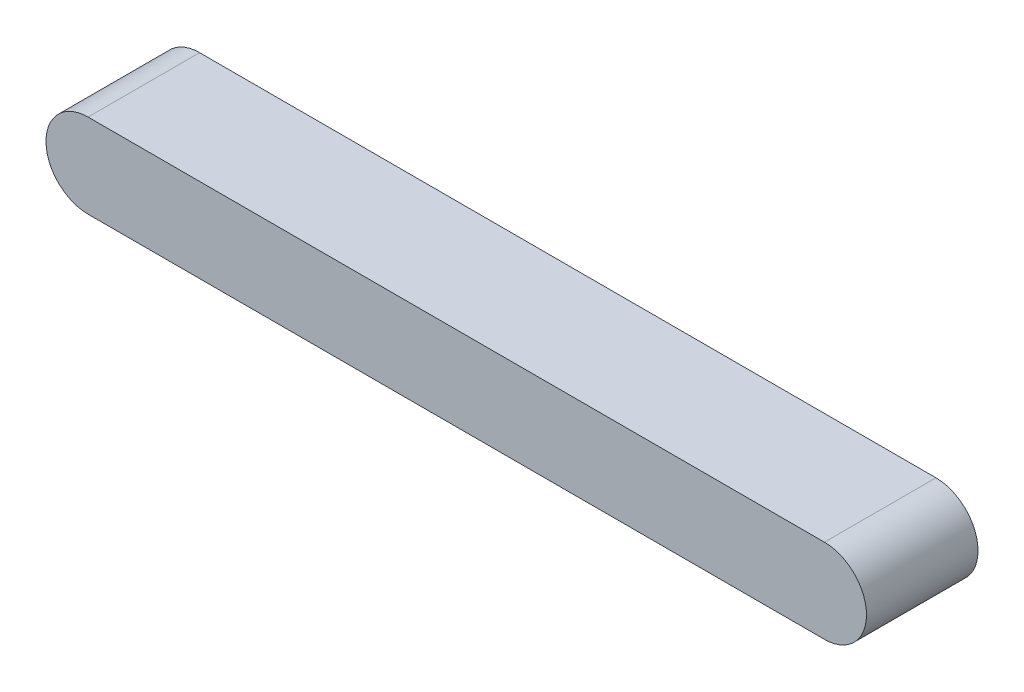
SolidWorks part; units mm, degrees
ref_plane "Alzado" through (0, 0, 0) normal (0, 0, 1) x (1, 0, 0)
ref_plane "Planta" through (0, 0, 0) normal (0, 1, 0) x (1, 0, 0)
ref_plane "Vista lateral" through (0, 0, 0) normal (1, 0, 0) x (0, 0, -1)
sketch "Croquis1" plane through (0, 0, 0) normal (0, 0, 1) x (1, 0, 0)
  line L0 (0, 0) -> (35, 0) construction
  line L1 (0, 2) -> (35, 2)
  line L2 (0, -2) -> (35, -2)
  arc A0 (0, 2) -> (0, -2) centre (0, 0) ccw
  arc A1 (35, -2) -> (35, 2) centre (35, 0) ccw
  point P3 (17.5, 0)
  dimension "D2" = 2
  dimension "D1" = 35
extrude "Saliente-Extruir1" add sketch "Croquis1" along normal blind 5.3
